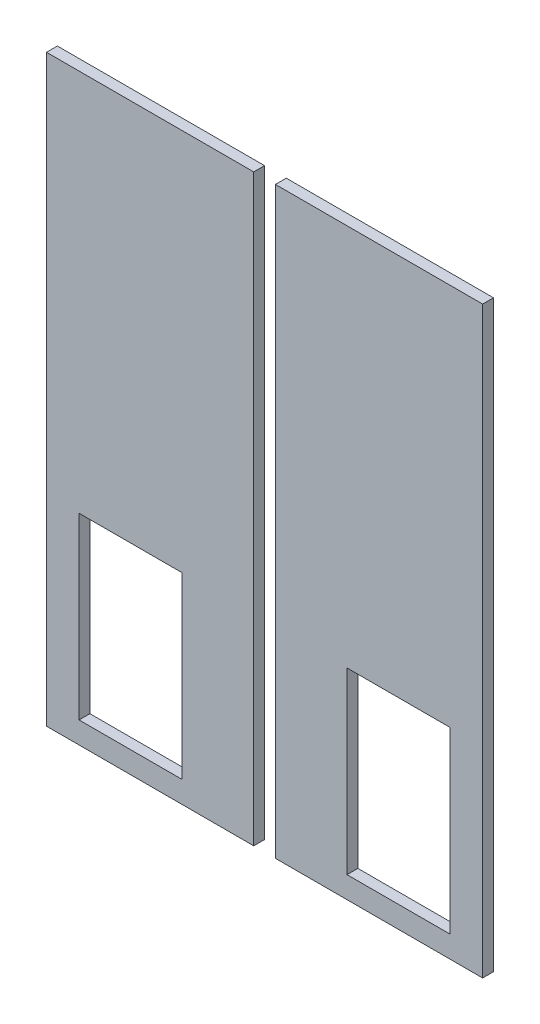
SolidWorks part; units mm, degrees
material "Oak"
ref_plane "Front Plane" through (0, 0, 0) normal (0, 0, 1) x (1, 0, 0)
ref_plane "Top Plane" through (0, 0, 0) normal (0, 1, 0) x (1, 0, 0)
ref_plane "Right Plane" through (0, 0, 0) normal (1, 0, 0) x (0, 0, -1)
sketch "Sketch1" plane through (0, 0, 0) normal (0, 0, 1) x (1, 0, 0)
  line L0 (-242.57, 341.63) -> (-242.57, -341.63) construction
  line L1 (-255.27, 341.63) -> (255.27, 341.63)
  line L2 (-255.27, 341.63) -> (-255.27, -341.63)
  line L3 (-255.27, -341.63) -> (255.27, -341.63)
  line L4 (255.27, 341.63) -> (255.27, -341.63)
  line L5 (-255.27, 341.63) -> (255.27, -341.63) construction
  line L6 (-255.27, -341.63) -> (255.27, 341.63) construction
  line L7 (-217.17, 341.63) -> (-217.17, -341.63) construction
  line L8 (-255.27, -316.23) -> (255.27, -316.23) construction
  line L9 (-217.17, -106.68) -> (-96.52, -106.68)
  line L10 (-217.17, -316.23) -> (-102.87, -316.23) construction
  line L11 (-217.17, -316.23) -> (-217.17, -113.03) construction
  line L12 (-217.17, -113.03) -> (-102.87, -113.03) construction
  line L13 (-102.87, -316.23) -> (-102.87, -113.03) construction
  line L14 (-96.52, -316.23) -> (-96.52, -106.68)
  line L15 (-217.17, -106.68) -> (-217.17, -316.23)
  line L16 (-217.17, -316.23) -> (-96.52, -316.23)
  line L17 (0, 341.63) -> (0, -341.63) construction
  line L18 (217.17, -316.23) -> (96.52, -316.23)
  line L19 (96.52, -316.23) -> (96.52, -106.68)
  line L20 (217.17, -106.68) -> (217.17, -316.23)
  line L21 (217.17, -106.68) -> (96.52, -106.68)
  line L22 (-12.7, 341.63) -> (-12.7, -341.63)
  line L23 (12.7, 341.63) -> (12.7, -341.63)
  point P0 (0, 0)
  dimension "D1" = 510.54
  dimension "D2" = 683.26
  dimension "D3" = 12.7
  dimension "D5" = 25.4
  dimension "D6" = 114.3
  dimension "D7" = 203.2
  dimension "D4" = 25.4
  dimension "D8" = 6.35
  dimension "D9" = 12.7
  dimension "D10" = 12.7
extrude "Boss-Extrude1" add sketch "Sketch1" along normal blind 12.7 contours L22 L1 L2 L3 L16 L15 L9 L14 | L1 L23 L3 L4 L21 L20 L18 L19
